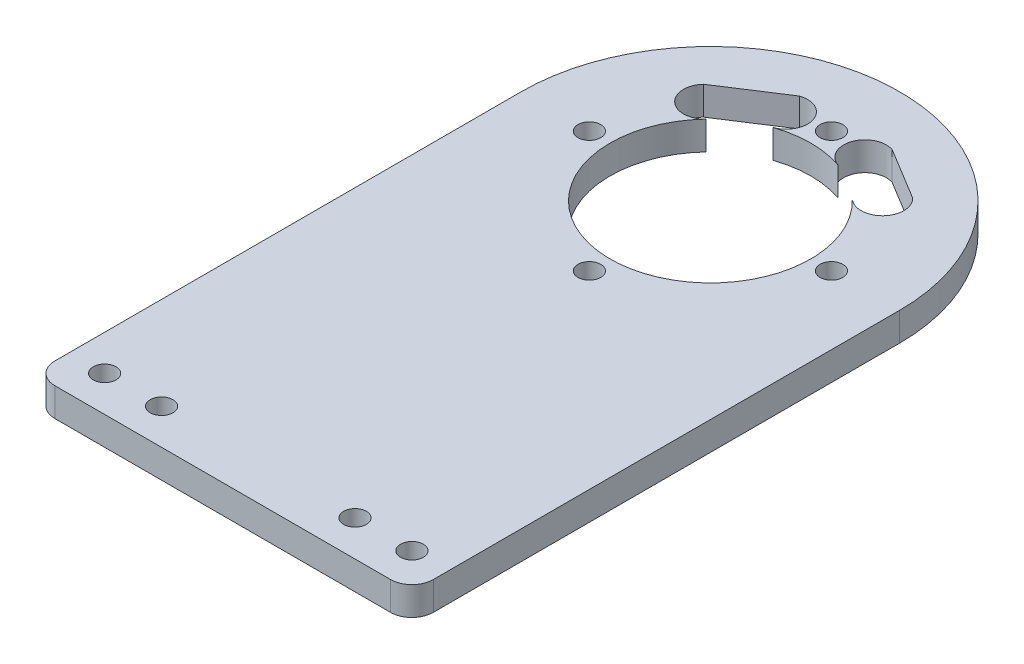
SolidWorks part; units mm, degrees
ref_plane "前视基准面" through (0, 0, 0) normal (0, 0, 1) x (1, 0, 0)
ref_plane "上视基准面" through (0, 0, 0) normal (0, 1, 0) x (1, 0, 0)
ref_plane "右视基准面" through (0, 0, 0) normal (1, 0, 0) x (0, 0, -1)
sketch "草图1" plane through (0, 0, 0) normal (0, 1, 0) x (1, 0, 0)
  line L0 (-26.5803, 0) -> (-26.5803, -68.5044)
  line L1 (26.5803, 0) -> (26.5803, -68.5044)
  line L2 (-14.695, 13.7132) -> (-6.5152, 19.0147)
  line L3 (6.5152, 19.0147) -> (13.8578, 14.5589)
  line L4 (-26.5803, -68.5044) -> (26.5803, -68.5044)
  line L5 (0, 26.5803) -> (0, -87.3272) construction
  line L6 (-59.7337, -52.5044) -> (80.5924, -52.5044) construction
  arc A0 (-4.5606, 13.3421) -> (4.5606, 13.3421) centre (0, 0) cw
  circle A1 centre (17, 0) radius 1.6
  circle A2 centre (-17, 0) radius 1.6
  circle A3 centre (0, 17) radius 1.6
  circle A4 centre (0, -17) radius 1.6
  arc A5 (-26.5803, 0) -> (26.5803, 0) centre (0, 0) cw
  arc A6 (-10.2865, 9.6435) -> (9.7005, 10.2328) centre (0, 0) ccw
  arc A7 (-14.695, 13.7132) -> (-10.2865, 9.6435) centre (-12.4752, 11.6953) ccw
  arc A8 (-6.5152, 19.0147) -> (-4.5606, 13.3421) centre (-5.5309, 16.1808) cw
  arc A9 (6.5152, 19.0147) -> (4.5606, 13.3421) centre (5.5309, 16.1808) ccw
  arc A10 (13.8578, 14.5589) -> (9.7005, 10.2328) centre (11.7644, 12.41) cw
  dimension "D2" = 3.2
  dimension "D4" = 26.5803
  dimension "D3" = 14.1
  dimension "D5" = 3
  dimension "D6" = 4.5606
  dimension "D7" = 6.5152
  dimension "D9" = 9.7005
  dimension "D10" = 10.2865
  dimension "D11" = 17
  dimension "D12" = 13.8578
  dimension "D13" = 17
  dimension "D14" = 17
  dimension "D17" = 68.5044
  dimension "D20" = 14.695
  dimension "D21" = 17
extrude "凸台-拉伸1" add sketch "草图1" along normal blind 4
sketch "草图2" plane through (0, 0, 0) normal (0, -1, 0) x (1, 0, 0)
  line L0 (0, 18.6) -> (0, 68.5044) construction
  line L1 (-26.5803, 68.5044) -> (26.5803, 68.5044) construction
  line L2 (26.5803, 68.5044) -> (26.5803, 0) construction
  circle A0 centre (0, 17) radius 1.6 construction
  circle A1 centre (21.5803, 63.5044) radius 1.6
  circle A2 centre (13.5803, 63.5044) radius 1.6
  circle A3 centre (-13.5803, 63.5044) radius 1.6
  circle A4 centre (-21.5803, 63.5044) radius 1.6
  dimension "D1" = 5
  dimension "D2" = 3.2
  dimension "D3" = 5
  dimension "D4" = 8
extrude "切除-拉伸1" cut sketch "草图2" against normal blind 10
fillet "圆角1" radius 3 2 edges at (-26.5803, 2, 68.5044) (26.5803, 2, 68.5044)
